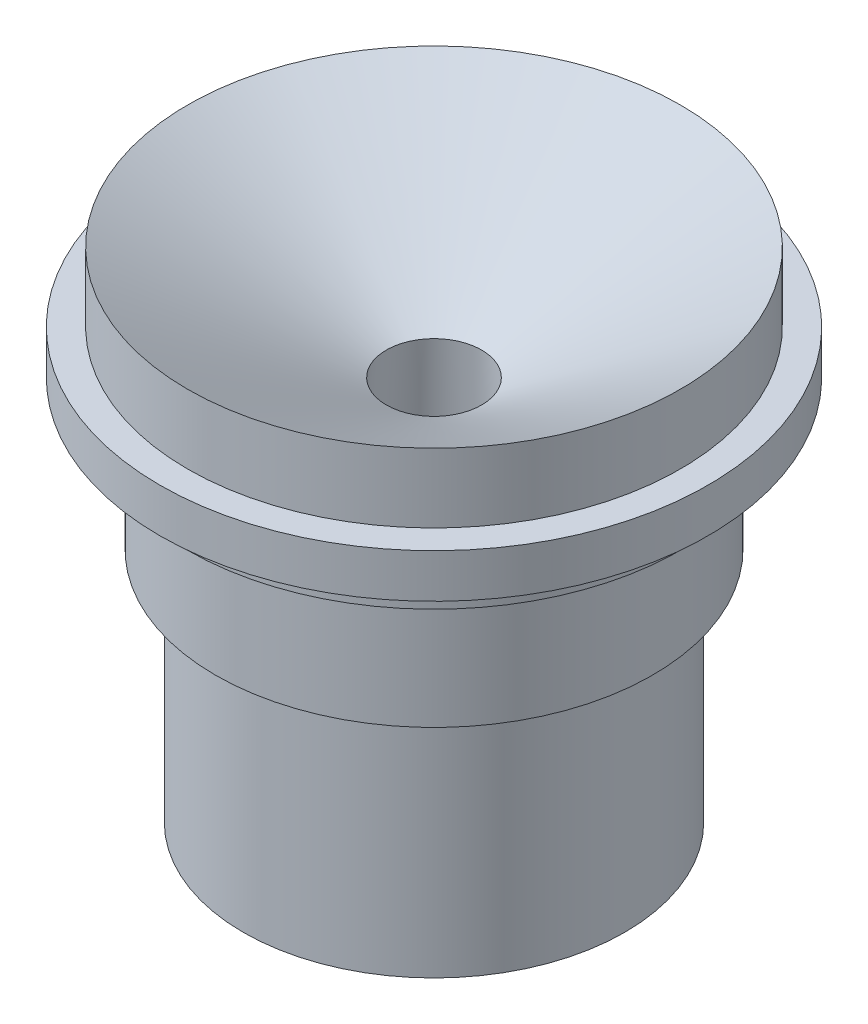
SolidWorks part; units mm, degrees
ref_plane "Front Plane" through (0, 0, 0) normal (0, 0, 1) x (1, 0, 0)
ref_plane "Top Plane" through (0, 0, 0) normal (0, 1, 0) x (1, 0, 0)
ref_plane "Right Plane" through (0, 0, 0) normal (1, 0, 0) x (0, 0, -1)
sketch "Sketch2" plane through (0, 0, 0) normal (0, 0, 1) x (1, 0, 0)
  line L0 (34.29, 0) -> (-34.29, 0)
  line L1 (-34.29, 0) -> (-34.29, 42.545)
  line L2 (-34.29, 42.545) -> (-39.29, 42.545)
  line L3 (-39.29, 42.545) -> (-39.29, 64.4865)
  line L4 (-39.29, 64.4865) -> (-44.29, 64.4865)
  line L5 (-44.29, 64.4865) -> (-44.29, 69.2546)
  line L6 (-44.29, 69.2546) -> (-49.29, 69.2546)
  line L7 (-49.29, 69.2546) -> (-49.29, 77.1376)
  line L8 (-49.29, 77.1376) -> (-44.29, 77.1376)
  line L9 (-44.29, 77.1376) -> (-44.29, 89.5587)
  line L10 (-44.29, 89.5587) -> (44.29, 89.5587)
  line L11 (0, 89.5587) -> (0, 0) construction
  line L12 (49.29, 69.2546) -> (49.29, 77.1376)
  line L13 (44.29, 77.1376) -> (44.29, 89.5587)
  line L14 (49.29, 77.1376) -> (44.29, 77.1376)
  line L15 (44.29, 69.2546) -> (49.29, 69.2546)
  line L16 (44.29, 64.4865) -> (44.29, 69.2546)
  line L17 (39.29, 64.4865) -> (44.29, 64.4865)
  line L18 (39.29, 42.545) -> (39.29, 64.4865)
  line L19 (34.29, 42.545) -> (39.29, 42.545)
  line L20 (34.29, 0) -> (34.29, 42.545)
  line L21 (8.5663, 69.2546) -> (-8.5663, 69.2546)
  line L22 (-8.5663, 69.2546) -> (-13.2684, 0)
  line L23 (8.5663, 69.2546) -> (13.2684, 0)
  line L24 (-8.5663, 69.2546) -> (-44.29, 89.5587)
  line L25 (8.5663, 69.2546) -> (44.29, 89.5587)
  point P27 (0, 69.2546)
  dimension "D1" = 7.883
  dimension "D2" = 68.58
  dimension "D3" = 42.545
  dimension "D4" = 5
  dimension "D5" = 5
  dimension "D6" = 5
revolve "Revolve2" add sketch "Sketch2" angle 360 about L11
